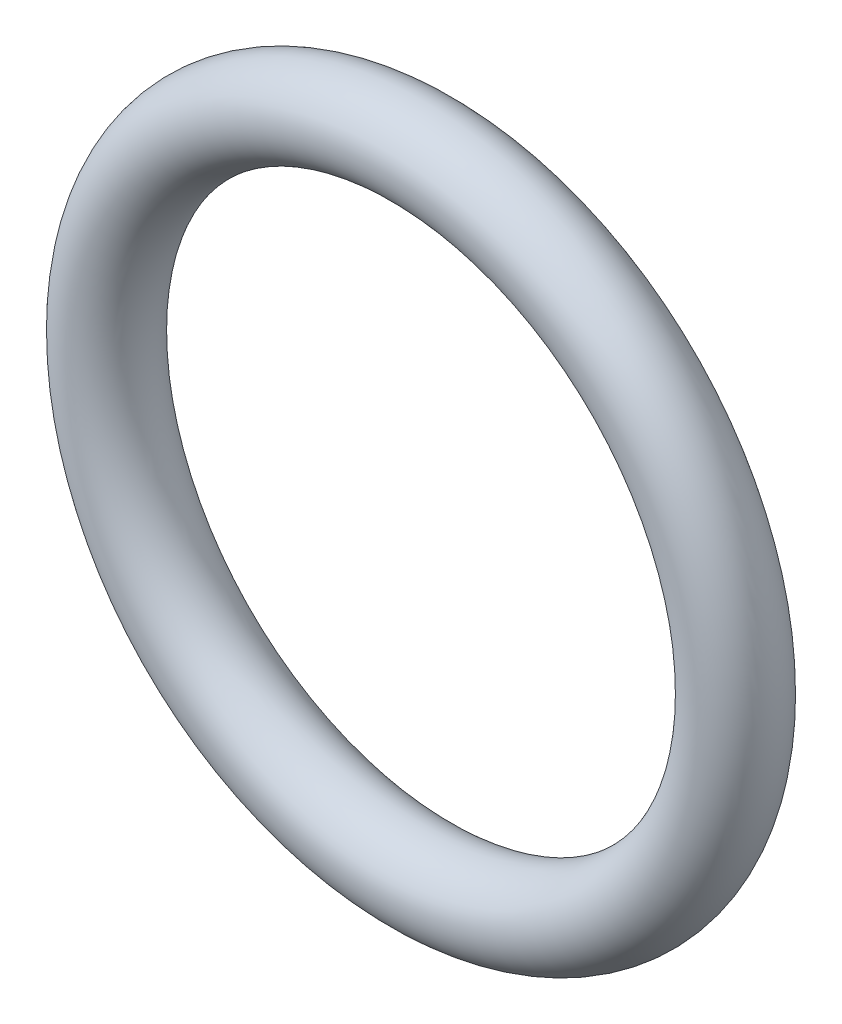
SolidWorks part; units mm, degrees
material "Резина"
ref_plane "Спереди" through (0, 0, 0) normal (0, 0, 1) x (1, 0, 0)
ref_plane "Сверху" through (0, 0, 0) normal (0, 1, 0) x (1, 0, 0)
ref_plane "Справа" through (0, 0, 0) normal (1, 0, 0) x (0, 0, -1)
sketch "Эскиз1" plane through (0, 0, 0) normal (0, 1, 0) x (1, 0, 0)
  line L0 (0, 0) -> (0, 5.3333) construction
  circle A0 centre (9.25, 0) radius 1.25
  point P2 (10.5, 0)
  dimension "D1" = 2.5
  dimension "D2" = 21
revolve "Повернуть1" add sketch "Эскиз1" angle 360 about L0
